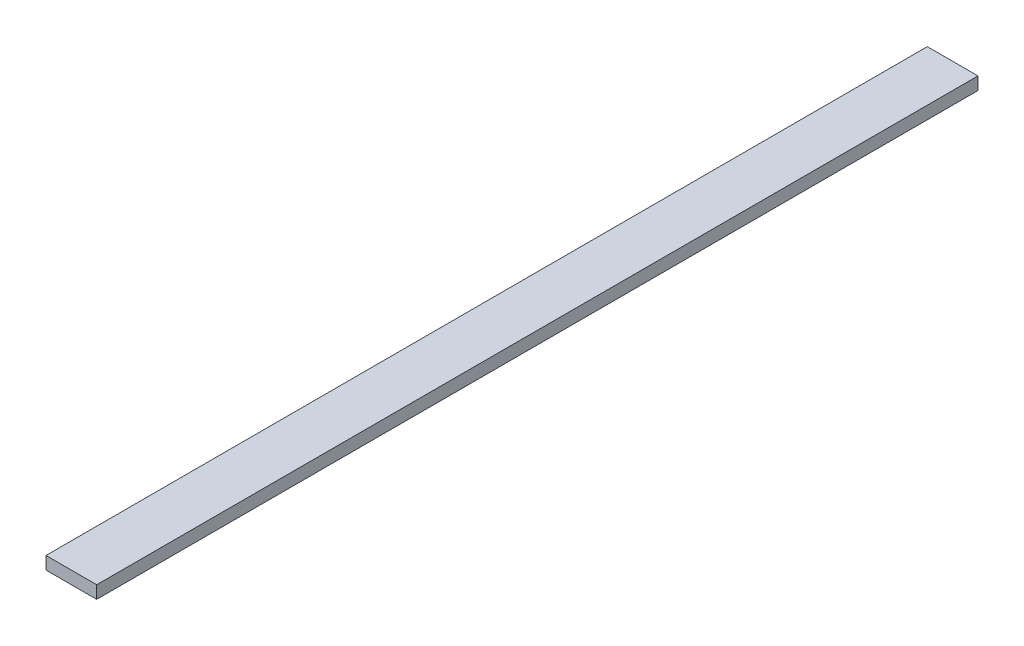
SolidWorks part; units mm, degrees
ref_plane "Front Plane" through (0, 0, 0) normal (0, 0, 1) x (1, 0, 0)
ref_plane "Top Plane" through (0, 0, 0) normal (0, 1, 0) x (1, 0, 0)
ref_plane "Right Plane" through (0, 0, 0) normal (1, 0, 0) x (0, 0, -1)
sketch "Sketch1" plane through (0, 0, 0) normal (0, 1, 0) x (1, 0, 0)
  line L1 (0, 0) -> (4, 0)
  line L2 (0, 0) -> (0, -69.55)
  line L3 (0, -69.55) -> (4, -69.55)
  line L4 (4, 0) -> (4, -69.55)
  dimension "D1" = 69.55
  dimension "D2" = 4
extrude "Boss-Extrude1" add sketch "Sketch1" along normal blind 1
